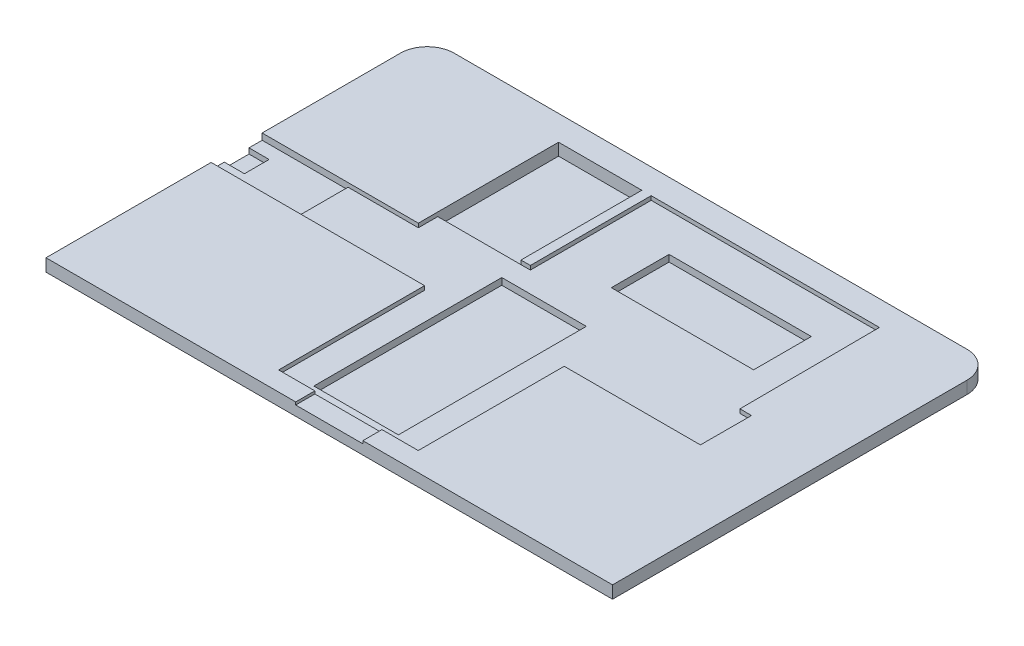
SolidWorks part; units mm, degrees
ref_plane "Front Plane" through (0, 0, 0) normal (0, 0, 1) x (1, 0, 0)
ref_plane "Top Plane" through (0, 0, 0) normal (0, 1, 0) x (1, 0, 0)
ref_plane "Right Plane" through (0, 0, 0) normal (1, 0, 0) x (0, 0, -1)
sketch "Sketch1" plane through (0, 0, 0) normal (0, 1, 0) x (1, 0, 0)
  line L1 (0, 0) -> (211, 0)
  line L2 (0, 0) -> (0, 132)
  line L3 (10, 142) -> (201, 142)
  line L4 (211, 0) -> (211, 132)
  arc A0 (201, 142) -> (211, 132) centre (201, 132) cw
  arc A1 (0, 132) -> (10, 142) centre (10, 132) cw
  dimension "D3" = 10
  dimension "D1" = 142
  dimension "D2" = 211
extrude "Boss-Extrude1" add sketch "Sketch1" along normal blind 4.65
sketch "Sketch2" plane through (0, 4.65, 0) normal (0, 1, 0) x (1, 0, 0)
  line L0 (0, 132) -> (0, 0) construction
  line L1 (0, 80.5) -> (32, 80.5)
  line L2 (0, 80.5) -> (0, 61.5)
  line L3 (0, 61.5) -> (32, 61.5)
  line L4 (32, 80.5) -> (32, 61.5)
  line L5 (0, 0) -> (211, 0) construction
  dimension "D1" = 32
  dimension "D2" = 19
  dimension "D3" = 61.5
extrude "Cut-Extrude1" cut sketch "Sketch2" against normal blind 2.35
sketch "Sketch3" plane through (0, 2.3, 0) normal (0, 1, 0) x (1, 0, 0)
  line L0 (0, 80.5) -> (0, 61.5) construction
  line L1 (0, 66.4) -> (7.5, 66.4)
  line L2 (0, 66.4) -> (0, 75.6)
  line L3 (0, 75.6) -> (7.5, 75.6)
  line L4 (7.5, 66.4) -> (7.5, 75.6)
  line L5 (0, 71) -> (7.5, 71) construction
  line L6 (0, 61.5) -> (32, 61.5) construction
  dimension "D1" = 9.2
  dimension "D2" = 7.5
  dimension "D3" = 9.5
extrude "Cut-Extrude2" cut sketch "Sketch3" against normal blind 2
sketch "Sketch4" plane through (0, 4.65, 0) normal (0, 1, 0) x (1, 0, 0)
  line L1 (58.1813, 87.7183) -> (89.1813, 87.7183)
  line L2 (58.1813, 87.7183) -> (58.1813, 132.7183)
  line L3 (58.1813, 132.7183) -> (89.1813, 132.7183)
  line L4 (89.1813, 87.7183) -> (89.1813, 132.7183)
  dimension "D1" = 45
  dimension "D2" = 31
extrude "Cut-Extrude3" cut sketch "Sketch4" against normal blind 4.5
sketch "Sketch5" plane through (0, 4.65, 0) normal (0, 1, 0) x (1, 0, 0)
  line L1 (113.4273, 97.1219) -> (166.4273, 97.1219)
  line L2 (113.4273, 97.1219) -> (113.4273, 118.6219)
  line L3 (113.4273, 118.6219) -> (166.4273, 118.6219)
  line L4 (166.4273, 97.1219) -> (166.4273, 118.6219)
  dimension "D1" = 53
  dimension "D2" = 21.5
extrude "Cut-Extrude4" cut sketch "Sketch5" against normal blind 4
sketch "Sketch6" plane through (0, 4.65, 0) normal (0, 1, 0) x (1, 0, 0)
  line L1 (32, 61.5) -> (79.5, 61.5)
  line L2 (32, 61.5) -> (32, 80.5)
  line L3 (32, 80.5) -> (58.1813, 80.5)
  line L5 (58.1813, 132.7183) -> (89.1813, 132.7183)
  line L9 (92.679, 132.72) -> (177.679, 132.72)
  line L14 (89.1813, 132.7183) -> (89.1813, 87.7183)
  line L15 (58.1813, 132.7183) -> (58.1813, 80.5)
  line L16 (92.679, 132.72) -> (92.679, 87.7183)
  line L17 (177.679, 132.72) -> (177.9496, 80.5)
  line L18 (177.9496, 80.5) -> (182.2619, 80.5)
  line L20 (182.2619, 80.5) -> (182.2271, 61.5)
  line L21 (89.1813, 87.7183) -> (92.679, 87.7183)
  line L22 (58.1813, 87.7183) -> (89.1813, 87.7183) construction
  line L23 (131.5, 61.5) -> (182.2271, 61.5)
  line L25 (131.5, 61.5) -> (131.5, 7.1362)
  line L26 (131.5, 7.1362) -> (79.5, 7.1362)
  line L27 (79.5, 61.5) -> (79.5, 7.1362)
  line L28 (211, 0) -> (211, 132) construction
  dimension "D1" = 52
  dimension "D2" = 31
  dimension "D3" = 85
  dimension "D4" = 79.5
extrude "Cut-Extrude5" cut sketch "Sketch6" against normal blind 1.5
sketch "Sketch7" plane through (0, 4.65, 0) normal (0, 1, 0) x (1, 0, 0)
  line L0 (0, 0) -> (211, 0) construction
  line L1 (118, 0) -> (93, 0)
  line L2 (118, 0) -> (118, 13.9678)
  line L3 (118, 13.9678) -> (93, 13.9678)
  line L4 (93, 0) -> (93, 13.9678)
  line L6 (0, 61.5) -> (0, 0) construction
  dimension "D1" = 25
  dimension "D2" = 93
extrude "Cut-Extrude6" cut sketch "Sketch7" against normal blind 1
sketch "Sketch9" plane through (0, 4.65, 0) normal (0, 1, 0) x (1, 0, 0)
  line L0 (93, 7.1362) -> (93, 0) construction
  line L1 (121.25, 79.9975) -> (89.75, 79.9975)
  line L2 (121.25, 79.9975) -> (121.25, 9.9975)
  line L3 (121.25, 9.9975) -> (89.75, 9.9975)
  line L4 (89.75, 79.9975) -> (89.75, 9.9975)
  dimension "D1" = 31.5
  dimension "D2" = 70
  dimension "D3" = 3.25
extrude "Cut-Extrude8" cut sketch "Sketch9" against normal blind 4
